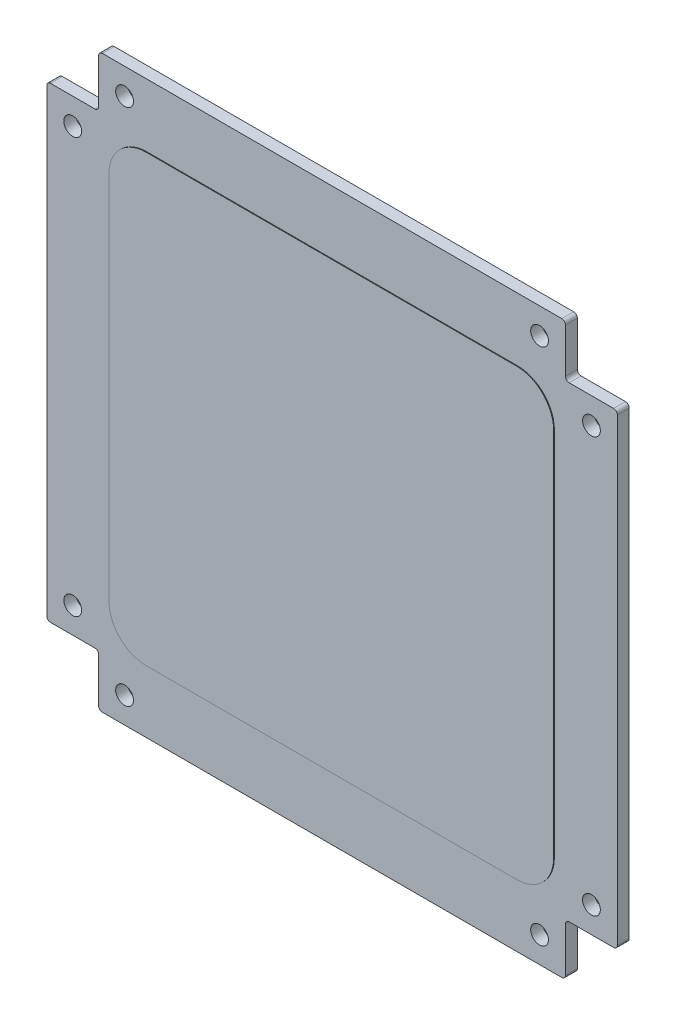
SolidWorks part; units mm, degrees
material "PET"
ref_plane "Front Plane" through (0, 0, 0) normal (0, 0, 1) x (1, 0, 0)
ref_plane "Top Plane" through (0, 0, 0) normal (0, 1, 0) x (1, 0, 0)
ref_plane "Right Plane" through (0, 0, 0) normal (1, 0, 0) x (0, 0, -1)
sketch "Sketch1" plane through (0, 0, 0) normal (0, 0, 1) x (1, 0, 0)
  line L0 (-31.5, 38) -> (-31.5, 32)
  line L1 (-31, -38.5) -> (31, -38.5)
  line L2 (-38.5, 31) -> (-38.5, -31)
  line L3 (-31, 38.5) -> (31, 38.5)
  line L4 (38.5, -31) -> (38.5, 31)
  line L5 (31.5, -38) -> (31.5, -32)
  line L6 (32, -31.5) -> (38, -31.5)
  line L7 (-32, 31.5) -> (-38, 31.5)
  line L8 (31.5, 38) -> (31.5, 32)
  line L9 (32, 31.5) -> (38, 31.5)
  line L10 (-38, -31.5) -> (-32, -31.5)
  line L11 (-31.5, -32) -> (-31.5, -38)
  line L12 (-32, -32) -> (32, 32) construction
  line L13 (32, -32) -> (-32, 32) construction
  arc A0 (-31, 38.5) -> (-31.5, 38) centre (-31, 38) ccw
  arc A1 (31, 38.5) -> (31.5, 38) centre (31, 38) cw
  arc A2 (31.5, 32) -> (32, 31.5) centre (32, 32) ccw
  arc A3 (38, 31.5) -> (38.5, 31) centre (38, 31) cw
  arc A4 (31, -38.5) -> (31.5, -38) centre (31, -38) ccw
  arc A5 (32, -31.5) -> (31.5, -32) centre (32, -32) ccw
  arc A6 (38, -31.5) -> (38.5, -31) centre (38, -31) ccw
  arc A7 (-31.5, -38) -> (-31, -38.5) centre (-31, -38) ccw
  arc A8 (-31.5, -32) -> (-32, -31.5) centre (-32, -32) ccw
  arc A9 (-38.5, -31) -> (-38, -31.5) centre (-38, -31) ccw
  arc A10 (-38, 31.5) -> (-38.5, 31) centre (-38, 31) ccw
  arc A11 (-32, 31.5) -> (-31.5, 32) centre (-32, 32) ccw
  point P0 (0, 0)
  dimension "D4" = 0.5
  dimension "D1" = 7
  dimension "D2" = 7
  dimension "D3" = 7
  dimension "D5" = 7
  dimension "D6" = 7
  dimension "D7" = 7
  dimension "D8" = 7
  dimension "D9" = 7
  dimension "D10" = 77
  dimension "D11" = 77
extrude "Boss-Extrude1" add sketch "Sketch1" along normal blind 1.6
sketch "Esboço1" plane through (0, 0, 1.6) normal (0, 0, 1) x (1, 0, 0)
  line L1 (-25, -30) -> (25, -30)
  line L2 (-30, -25) -> (-30, 25)
  line L3 (-25, 30) -> (25, 30)
  line L4 (30, -25) -> (30, 25)
  line L5 (-25, -25) -> (25, 25) construction
  line L6 (-25, 25) -> (25, -25) construction
  arc A0 (-30, 25) -> (-25, 30) centre (-25, 25) cw
  arc A1 (25, 30) -> (30, 25) centre (25, 25) cw
  arc A2 (30, -25) -> (25, -30) centre (25, -25) cw
  arc A3 (-25, -30) -> (-30, -25) centre (-25, -25) cw
  point P0 (0, 0)
  dimension "D1" = 5
  dimension "D2" = 60
  dimension "D3" = 60
extrude "Boss-Extrude2" add sketch "Esboço1" along normal blind 0.1
hole_wizard "M2 Hole1-FixingStructure" positions "Sketch3" profile "Sketch2" hole size "M2" standard "DIN"
sketch "Sketch3" plane through (0, 0, 0) normal (0, 0, -1) x (-1, 0, 0)
  line L0 (-31, 38.5) -> (31, 38.5) construction
  line L1 (31, -38.5) -> (-31, -38.5) construction
  line L2 (-38.5, -31) -> (-38.5, 31) construction
  line L3 (38.5, 31) -> (38.5, -31) construction
  line L4 (-31, 38.5) -> (31, 38.5) construction
  line L5 (31, -38.5) -> (-31, -38.5) construction
  line L6 (38.5, 31) -> (38.5, -31) construction
  line L7 (-38.5, -31) -> (-38.5, 31) construction
  point P0 (-28, 35)
  point P2 (28, 35)
  point P4 (-28, -35)
  point P6 (28, -35)
  point P20 (35, 28)
  point P22 (35, -28)
  point P24 (-35, -28)
  point P26 (-35, 28)
  dimension "D1" = 3.5
  dimension "D2" = 3.5
  dimension "D3" = 10.5
  dimension "D4" = 10.5
  dimension "D5" = 10.5
  dimension "D6" = 10.5
  dimension "D7" = 3.5
  dimension "D8" = 3.5
sketch "Sketch2" plane through (28, 35, 0) normal (1, 0, 0) x (0, 1, 0)
  line L0 (0, 0) -> (0, 200.721)
  line L1 (0, 200.721) -> (1.2, 200)
  line L2 (1.2, 200) -> (1.2, 0)
  line L5 (1.2, 0) -> (0, 0)
  line L10 (0, 200.721) -> (-1.2, 200) construction
  line L11 (0, -6.35) -> (0, 107.95) construction
  dimension "Hole Dia." = 2.4
  dimension "Hole Depth" = 200
  dimension "Drill Angle" = 118
